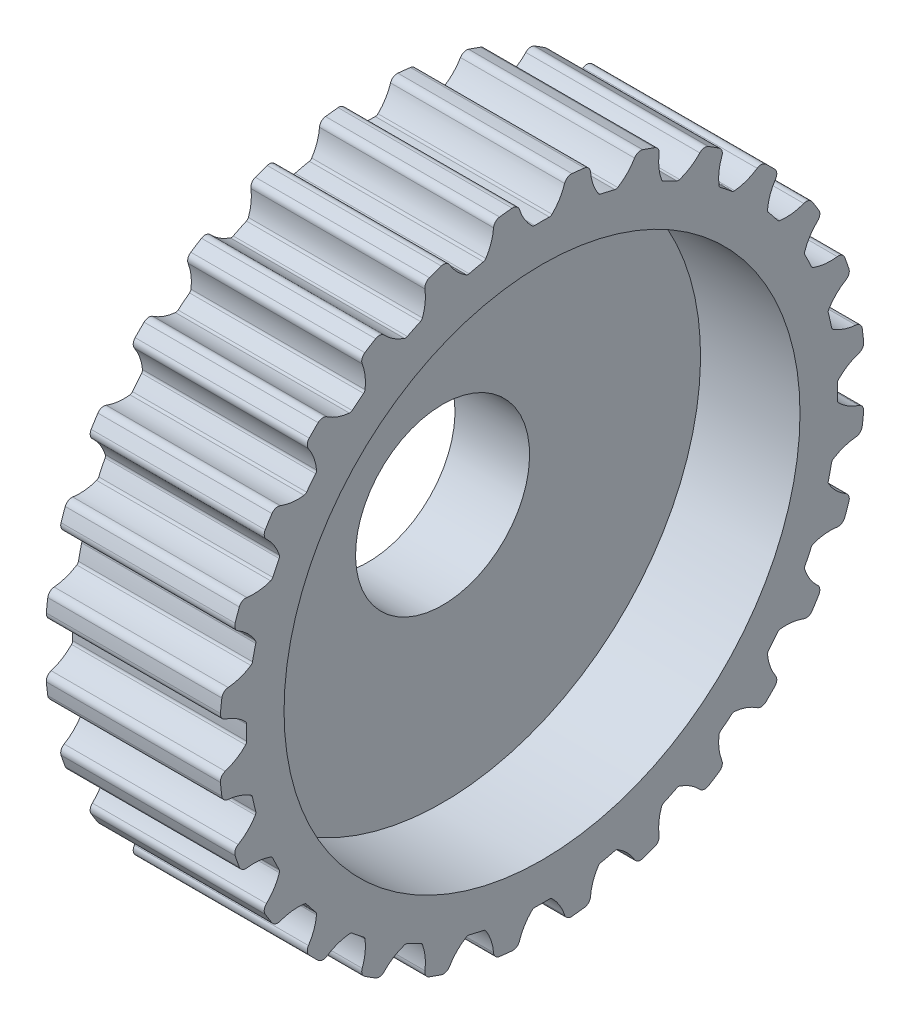
SolidWorks part; units mm, degrees
material "Vero PureWhite"
ref_plane "前视基准面" through (0, 0, 0) normal (0, 0, 1) x (1, 0, 0)
ref_plane "上视基准面" through (0, 0, 0) normal (0, 1, 0) x (1, 0, 0)
ref_plane "右视基准面" through (0, 0, 0) normal (1, 0, 0) x (0, 0, -1)
other "Configuration Table"
ref_plane "基准面1" through (0, 0, 0) normal (0, 0, 1) x (1, 0, 0)
sketch "草图1" plane through (0, 0, 0) normal (0, 0, 1) x (1, 0, 0)
  line L0 (0, 0) -> (0, 10)
  line L1 (0, 10) -> (1, 10)
  line L2 (1, 10) -> (1, 12.8583)
  line L3 (1, 12.8583) -> (0.4955, 14.7412)
  line L4 (0.4955, 14.7412) -> (1.4614, 15)
  line L5 (1.4614, 15) -> (2, 12.99)
  line L6 (2, 12.99) -> (9, 12.99)
  line L7 (9, 12.99) -> (9.5386, 15)
  line L8 (9.5386, 15) -> (10.5045, 14.7412)
  line L9 (10.5045, 14.7412) -> (10, 12.8583)
  line L10 (10, 12.8583) -> (10, 10)
  line L11 (10, 10) -> (11, 10)
  line L12 (11, 10) -> (11, 0)
  line L13 (11, 0) -> (0, 0)
  line L14 (11, 0) -> (0, 0) construction
revolve "旋转1" add sketch "草图1" angle 360 about L14
ref_plane "基准面2" through (0, 0, 0) normal (0, 0, 1) x (1, 0, 0)
sketch "草图2" plane through (0, 0, 0) normal (0, 0, 1) x (1, 0, 0)
  line L0 (0, 0) -> (0, 3.5)
  line L1 (0, 3.5) -> (11, 3.5)
  line L2 (11, 3.5) -> (11, 0)
  line L3 (11, 0) -> (0, 0)
  line L4 (11, 0) -> (0, 0) construction
  point P4 (0, 0)
  point P6 (0, 3.5)
  point P7 (10.9, 0.0386)
  point P9 (10.9, 0)
  point P10 (11, 0)
  point P11 (10.9, 3.3)
  point P13 (11, 3.3)
  point P14 (11, 3.5)
  dimension "D1" = 3.5
revolve "切除-旋转1" cut sketch "草图2" angle 360 about L4
ref_plane "基准面3" through (2, 0, 0) normal (1, 0, 0) x (0, 0, -1)
sketch "草图3" plane through (2, 0, 0) normal (1, 0, 0) x (0, 0, -1)
  circle A0 centre (0, 0) radius 17.99
  arc A1 (-12.9343, 1.2013) -> (-12.7398, 0.9084) centre (-12.6555, 1.1754) ccw
  arc A2 (-12.7398, 0.9084) -> (-11.9188, 0.4022) centre (-13.3344, -0.975) cw
  arc A3 (-11.9188, 0.4022) -> (-11.8764, 0.2939) centre (-12.0263, 0.2976) cw
  arc A4 (-11.8764, 0.2939) -> (-11.8764, -0.2939) centre (0, 0) ccw
  arc A5 (-11.8764, -0.2939) -> (-11.9188, -0.4022) centre (-12.0263, -0.2976) cw
  arc A6 (-11.9188, -0.4022) -> (-12.7398, -0.9084) centre (-13.3344, 0.975) cw
  arc A7 (-12.7398, -0.9084) -> (-12.9343, -1.2013) centre (-12.6555, -1.1754) ccw
  arc A8 (-12.9343, -1.2013) -> (-12.8774, -1.707) centre (0, 0) ccw
  arc A9 (-12.8774, -1.707) -> (-12.6225, -1.9493) centre (-12.5998, -1.6702) ccw
  arc A10 (-12.6225, -1.9493) -> (-11.7095, -2.2601) centre (-12.7831, -3.9177) cw
  arc A11 (-11.7095, -2.2601) -> (-11.644, -2.3562) centre (-11.791, -2.386) cw
  arc A12 (-11.644, -2.3562) -> (-11.5132, -2.9293) centre (0, 0) ccw
  arc A13 (-11.5132, -2.9293) -> (-11.5305, -3.0443) centre (-11.6586, -2.9663) cw
  arc A14 (-11.5305, -3.0443) -> (-12.2183, -3.7205) centre (-13.217, -2.0166) cw
  arc A15 (-12.2183, -3.7205) -> (-12.3427, -4.0493) centre (-12.0767, -3.962) ccw
  arc A16 (-12.3427, -4.0493) -> (-12.1746, -4.5297) centre (0, 0) ccw
  arc A17 (-12.1746, -4.5297) -> (-11.8723, -4.7092) centre (-11.9122, -4.432) ccw
  arc A18 (-11.8723, -4.7092) -> (-10.913, -4.809) centre (-11.5908, -6.664) cw
  arc A19 (-10.913, -4.809) -> (-10.8278, -4.8882) centre (-10.9645, -4.9499) cw
  arc A20 (-10.8278, -4.8882) -> (-10.5727, -5.4178) centre (0, 0) ccw
  arc A21 (-10.5727, -5.4178) -> (-10.564, -5.5338) centre (-10.7062, -5.4862) cw
  arc A22 (-10.564, -5.5338) -> (-11.0841, -6.346) centre (-12.4369, -4.9071) cw
  arc A23 (-11.0841, -6.346) -> (-11.1322, -6.6943) centre (-10.8923, -6.55) ccw
  arc A24 (-11.1322, -6.6943) -> (-10.8615, -7.1252) centre (0, 0) ccw
  arc A25 (-10.8615, -7.1252) -> (-10.5268, -7.233) centre (-10.6273, -6.9716) ccw
  arc A26 (-10.5268, -7.233) -> (-9.5693, -7.1168) centre (-9.8174, -9.0761) cw
  arc A27 (-9.5693, -7.1168) -> (-9.4686, -7.175) centre (-9.5881, -7.2656) cw
  arc A28 (-9.4686, -7.175) -> (-9.1021, -7.6346) centre (0, 0) ccw
  arc A29 (-9.1021, -7.6346) -> (-9.0677, -7.7457) centre (-9.217, -7.731) cw
  arc A30 (-9.0677, -7.7457) -> (-9.394, -8.6534) centre (-11.0332, -7.5516) cw
  arc A31 (-9.394, -8.6534) -> (-9.3635, -9.0036) centre (-9.1617, -8.8096) ccw
  arc A32 (-9.3635, -9.0036) -> (-9.0036, -9.3635) centre (0, 0) ccw
  arc A33 (-9.0036, -9.3635) -> (-8.6534, -9.394) centre (-8.8096, -9.1617) ccw
  arc A34 (-8.6534, -9.394) -> (-7.7457, -9.0677) centre (-7.5516, -11.0332) cw
  arc A35 (-7.7457, -9.0677) -> (-7.6346, -9.1021) centre (-7.731, -9.217) cw
  arc A36 (-7.6346, -9.1021) -> (-7.175, -9.4686) centre (0, 0) ccw
  arc A37 (-7.175, -9.4686) -> (-7.1168, -9.5693) centre (-7.2656, -9.5881) cw
  arc A38 (-7.1168, -9.5693) -> (-7.233, -10.5268) centre (-9.0761, -9.8174) cw
  arc A39 (-7.233, -10.5268) -> (-7.1252, -10.8615) centre (-6.9716, -10.6273) ccw
  arc A40 (-7.1252, -10.8615) -> (-6.6943, -11.1322) centre (0, 0) ccw
  arc A41 (-6.6943, -11.1322) -> (-6.346, -11.0841) centre (-6.55, -10.8923) ccw
  arc A42 (-6.346, -11.0841) -> (-5.5338, -10.564) centre (-4.9071, -12.4369) cw
  arc A43 (-5.5338, -10.564) -> (-5.4178, -10.5727) centre (-5.4862, -10.7062) cw
  arc A44 (-5.4178, -10.5727) -> (-4.8882, -10.8278) centre (0, 0) ccw
  arc A45 (-4.8882, -10.8278) -> (-4.809, -10.913) centre (-4.9499, -10.9645) cw
  arc A46 (-4.809, -10.913) -> (-4.7092, -11.8723) centre (-6.664, -11.5908) cw
  arc A47 (-4.7092, -11.8723) -> (-4.5297, -12.1746) centre (-4.432, -11.9122) ccw
  arc A48 (-4.5297, -12.1746) -> (-4.0493, -12.3427) centre (0, 0) ccw
  arc A49 (-4.0493, -12.3427) -> (-3.7205, -12.2183) centre (-3.962, -12.0767) ccw
  arc A50 (-3.7205, -12.2183) -> (-3.0443, -11.5305) centre (-2.0166, -13.217) cw
  arc A51 (-3.0443, -11.5305) -> (-2.9293, -11.5132) centre (-2.9663, -11.6586) cw
  arc A52 (-2.9293, -11.5132) -> (-2.3562, -11.644) centre (0, 0) ccw
  arc A53 (-2.3562, -11.644) -> (-2.2601, -11.7095) centre (-2.386, -11.791) cw
  arc A54 (-2.2601, -11.7095) -> (-1.9493, -12.6225) centre (-3.9177, -12.7831) cw
  arc A55 (-1.9493, -12.6225) -> (-1.707, -12.8774) centre (-1.6702, -12.5998) ccw
  arc A56 (-1.707, -12.8774) -> (-1.2013, -12.9343) centre (0, 0) ccw
  arc A57 (-1.2013, -12.9343) -> (-0.9084, -12.7398) centre (-1.1754, -12.6555) ccw
  arc A58 (-0.9084, -12.7398) -> (-0.4022, -11.9188) centre (0.975, -13.3344) cw
  arc A59 (-0.4022, -11.9188) -> (-0.2939, -11.8764) centre (-0.2976, -12.0263) cw
  arc A60 (-0.2939, -11.8764) -> (0.2939, -11.8764) centre (0, 0) ccw
  arc A61 (0.2939, -11.8764) -> (0.4022, -11.9188) centre (0.2976, -12.0263) cw
  arc A62 (0.4022, -11.9188) -> (0.9084, -12.7398) centre (-0.975, -13.3344) cw
  arc A63 (0.9084, -12.7398) -> (1.2013, -12.9343) centre (1.1754, -12.6555) ccw
  arc A64 (1.2013, -12.9343) -> (1.707, -12.8774) centre (0, 0) ccw
  arc A65 (1.707, -12.8774) -> (1.9493, -12.6225) centre (1.6702, -12.5998) ccw
  arc A66 (1.9493, -12.6225) -> (2.2601, -11.7095) centre (3.9177, -12.7831) cw
  arc A67 (2.2601, -11.7095) -> (2.3562, -11.644) centre (2.386, -11.791) cw
  arc A68 (2.3562, -11.644) -> (2.9293, -11.5132) centre (0, 0) ccw
  arc A69 (2.9293, -11.5132) -> (3.0443, -11.5305) centre (2.9663, -11.6586) cw
  arc A70 (3.0443, -11.5305) -> (3.7205, -12.2183) centre (2.0166, -13.217) cw
  arc A71 (3.7205, -12.2183) -> (4.0493, -12.3427) centre (3.962, -12.0767) ccw
  arc A72 (4.0493, -12.3427) -> (4.5297, -12.1746) centre (0, 0) ccw
  arc A73 (4.5297, -12.1746) -> (4.7092, -11.8723) centre (4.432, -11.9122) ccw
  arc A74 (4.7092, -11.8723) -> (4.809, -10.913) centre (6.664, -11.5908) cw
  arc A75 (4.809, -10.913) -> (4.8882, -10.8278) centre (4.9499, -10.9645) cw
  arc A76 (4.8882, -10.8278) -> (5.4178, -10.5727) centre (0, 0) ccw
  arc A77 (5.4178, -10.5727) -> (5.5338, -10.564) centre (5.4862, -10.7062) cw
  arc A78 (5.5338, -10.564) -> (6.346, -11.0841) centre (4.9071, -12.4369) cw
  arc A79 (6.346, -11.0841) -> (6.6943, -11.1322) centre (6.55, -10.8923) ccw
  arc A80 (6.6943, -11.1322) -> (7.1252, -10.8615) centre (0, 0) ccw
  arc A81 (7.1252, -10.8615) -> (7.233, -10.5268) centre (6.9716, -10.6273) ccw
  arc A82 (7.233, -10.5268) -> (7.1168, -9.5693) centre (9.0761, -9.8174) cw
  arc A83 (7.1168, -9.5693) -> (7.175, -9.4686) centre (7.2656, -9.5881) cw
  arc A84 (7.175, -9.4686) -> (7.6346, -9.1021) centre (0, 0) ccw
  arc A85 (7.6346, -9.1021) -> (7.7457, -9.0677) centre (7.731, -9.217) cw
  arc A86 (7.7457, -9.0677) -> (8.6534, -9.394) centre (7.5516, -11.0332) cw
  arc A87 (8.6534, -9.394) -> (9.0036, -9.3635) centre (8.8096, -9.1617) ccw
  arc A88 (9.0036, -9.3635) -> (9.3635, -9.0036) centre (0, 0) ccw
  arc A89 (9.3635, -9.0036) -> (9.394, -8.6534) centre (9.1617, -8.8096) ccw
  arc A90 (9.394, -8.6534) -> (9.0677, -7.7457) centre (11.0332, -7.5516) cw
  arc A91 (9.0677, -7.7457) -> (9.1021, -7.6346) centre (9.217, -7.731) cw
  arc A92 (9.1021, -7.6346) -> (9.4686, -7.175) centre (0, 0) ccw
  arc A93 (9.4686, -7.175) -> (9.5693, -7.1168) centre (9.5881, -7.2656) cw
  arc A94 (9.5693, -7.1168) -> (10.5268, -7.233) centre (9.8174, -9.0761) cw
  arc A95 (10.5268, -7.233) -> (10.8615, -7.1252) centre (10.6273, -6.9716) ccw
  arc A96 (10.8615, -7.1252) -> (11.1322, -6.6943) centre (0, 0) ccw
  arc A97 (11.1322, -6.6943) -> (11.0841, -6.346) centre (10.8923, -6.55) ccw
  arc A98 (11.0841, -6.346) -> (10.564, -5.5338) centre (12.4369, -4.9071) cw
  arc A99 (10.564, -5.5338) -> (10.5727, -5.4178) centre (10.7062, -5.4862) cw
  arc A100 (10.5727, -5.4178) -> (10.8278, -4.8882) centre (0, 0) ccw
  arc A101 (10.8278, -4.8882) -> (10.913, -4.809) centre (10.9645, -4.9499) cw
  arc A102 (10.913, -4.809) -> (11.8723, -4.7092) centre (11.5908, -6.664) cw
  arc A103 (11.8723, -4.7092) -> (12.1746, -4.5297) centre (11.9122, -4.432) ccw
  arc A104 (12.1746, -4.5297) -> (12.3427, -4.0493) centre (0, 0) ccw
  arc A105 (12.3427, -4.0493) -> (12.2183, -3.7205) centre (12.0767, -3.962) ccw
  arc A106 (12.2183, -3.7205) -> (11.5305, -3.0443) centre (13.217, -2.0166) cw
  arc A107 (11.5305, -3.0443) -> (11.5132, -2.9293) centre (11.6586, -2.9663) cw
  arc A108 (11.5132, -2.9293) -> (11.644, -2.3562) centre (0, 0) ccw
  arc A109 (11.644, -2.3562) -> (11.7095, -2.2601) centre (11.791, -2.386) cw
  arc A110 (11.7095, -2.2601) -> (12.6225, -1.9493) centre (12.7831, -3.9177) cw
  arc A111 (12.6225, -1.9493) -> (12.8774, -1.707) centre (12.5998, -1.6702) ccw
  arc A112 (12.8774, -1.707) -> (12.9343, -1.2013) centre (0, 0) ccw
  arc A113 (12.9343, -1.2013) -> (12.7398, -0.9084) centre (12.6555, -1.1754) ccw
  arc A114 (12.7398, -0.9084) -> (11.9188, -0.4022) centre (13.3344, 0.975) cw
  arc A115 (11.9188, -0.4022) -> (11.8764, -0.2939) centre (12.0263, -0.2976) cw
  arc A116 (11.8764, -0.2939) -> (11.8764, 0.2939) centre (0, 0) ccw
  arc A117 (11.8764, 0.2939) -> (11.9188, 0.4022) centre (12.0263, 0.2976) cw
  arc A118 (11.9188, 0.4022) -> (12.7398, 0.9084) centre (13.3344, -0.975) cw
  arc A119 (12.7398, 0.9084) -> (12.9343, 1.2013) centre (12.6555, 1.1754) ccw
  arc A120 (12.9343, 1.2013) -> (12.8774, 1.707) centre (0, 0) ccw
  arc A121 (12.8774, 1.707) -> (12.6225, 1.9493) centre (12.5998, 1.6702) ccw
  arc A122 (12.6225, 1.9493) -> (11.7095, 2.2601) centre (12.7831, 3.9177) cw
  arc A123 (11.7095, 2.2601) -> (11.644, 2.3562) centre (11.791, 2.386) cw
  arc A124 (11.644, 2.3562) -> (11.5132, 2.9293) centre (0, 0) ccw
  arc A125 (11.5132, 2.9293) -> (11.5305, 3.0443) centre (11.6586, 2.9663) cw
  arc A126 (11.5305, 3.0443) -> (12.2183, 3.7205) centre (13.217, 2.0166) cw
  arc A127 (12.2183, 3.7205) -> (12.3427, 4.0493) centre (12.0767, 3.962) ccw
  arc A128 (12.3427, 4.0493) -> (12.1746, 4.5297) centre (0, 0) ccw
  arc A129 (12.1746, 4.5297) -> (11.8723, 4.7092) centre (11.9122, 4.432) ccw
  arc A130 (11.8723, 4.7092) -> (10.913, 4.809) centre (11.5908, 6.664) cw
  arc A131 (10.913, 4.809) -> (10.8278, 4.8882) centre (10.9645, 4.9499) cw
  arc A132 (10.8278, 4.8882) -> (10.5727, 5.4178) centre (0, 0) ccw
  arc A133 (10.5727, 5.4178) -> (10.564, 5.5338) centre (10.7062, 5.4862) cw
  arc A134 (10.564, 5.5338) -> (11.0841, 6.346) centre (12.4369, 4.9071) cw
  arc A135 (11.0841, 6.346) -> (11.1322, 6.6943) centre (10.8923, 6.55) ccw
  arc A136 (11.1322, 6.6943) -> (10.8615, 7.1252) centre (0, 0) ccw
  arc A137 (10.8615, 7.1252) -> (10.5268, 7.233) centre (10.6273, 6.9716) ccw
  arc A138 (10.5268, 7.233) -> (9.5693, 7.1168) centre (9.8174, 9.0761) cw
  arc A139 (9.5693, 7.1168) -> (9.4686, 7.175) centre (9.5881, 7.2656) cw
  arc A140 (9.4686, 7.175) -> (9.1021, 7.6346) centre (0, 0) ccw
  arc A141 (9.1021, 7.6346) -> (9.0677, 7.7457) centre (9.217, 7.731) cw
  arc A142 (9.0677, 7.7457) -> (9.394, 8.6534) centre (11.0332, 7.5516) cw
  arc A143 (9.394, 8.6534) -> (9.3635, 9.0036) centre (9.1617, 8.8096) ccw
  arc A144 (9.3635, 9.0036) -> (9.0036, 9.3635) centre (0, 0) ccw
  arc A145 (9.0036, 9.3635) -> (8.6534, 9.394) centre (8.8096, 9.1617) ccw
  arc A146 (8.6534, 9.394) -> (7.7457, 9.0677) centre (7.5516, 11.0332) cw
  arc A147 (7.7457, 9.0677) -> (7.6346, 9.1021) centre (7.731, 9.217) cw
  arc A148 (7.6346, 9.1021) -> (7.175, 9.4686) centre (0, 0) ccw
  arc A149 (7.175, 9.4686) -> (7.1168, 9.5693) centre (7.2656, 9.5881) cw
  arc A150 (7.1168, 9.5693) -> (7.233, 10.5268) centre (9.0761, 9.8174) cw
  arc A151 (7.233, 10.5268) -> (7.1252, 10.8615) centre (6.9716, 10.6273) ccw
  arc A152 (7.1252, 10.8615) -> (6.6943, 11.1322) centre (0, 0) ccw
  arc A153 (6.6943, 11.1322) -> (6.346, 11.0841) centre (6.55, 10.8923) ccw
  arc A154 (6.346, 11.0841) -> (5.5338, 10.564) centre (4.9071, 12.4369) cw
  arc A155 (5.5338, 10.564) -> (5.4178, 10.5727) centre (5.4862, 10.7062) cw
  arc A156 (5.4178, 10.5727) -> (4.8882, 10.8278) centre (0, 0) ccw
  arc A157 (4.8882, 10.8278) -> (4.809, 10.913) centre (4.9499, 10.9645) cw
  arc A158 (4.809, 10.913) -> (4.7092, 11.8723) centre (6.664, 11.5908) cw
  arc A159 (4.7092, 11.8723) -> (4.5297, 12.1746) centre (4.432, 11.9122) ccw
  arc A160 (4.5297, 12.1746) -> (4.0493, 12.3427) centre (0, 0) ccw
  arc A161 (4.0493, 12.3427) -> (3.7205, 12.2183) centre (3.962, 12.0767) ccw
  arc A162 (3.7205, 12.2183) -> (3.0443, 11.5305) centre (2.0166, 13.217) cw
  arc A163 (3.0443, 11.5305) -> (2.9293, 11.5132) centre (2.9663, 11.6586) cw
  arc A164 (2.9293, 11.5132) -> (2.3562, 11.644) centre (0, 0) ccw
  arc A165 (2.3562, 11.644) -> (2.2601, 11.7095) centre (2.386, 11.791) cw
  arc A166 (2.2601, 11.7095) -> (1.9493, 12.6225) centre (3.9177, 12.7831) cw
  arc A167 (1.9493, 12.6225) -> (1.707, 12.8774) centre (1.6702, 12.5998) ccw
  arc A168 (1.707, 12.8774) -> (1.2013, 12.9343) centre (0, 0) ccw
  arc A169 (1.2013, 12.9343) -> (0.9084, 12.7398) centre (1.1754, 12.6555) ccw
  arc A170 (0.9084, 12.7398) -> (0.4022, 11.9188) centre (-0.975, 13.3344) cw
  arc A171 (0.4022, 11.9188) -> (0.2939, 11.8764) centre (0.2976, 12.0263) cw
  arc A172 (0.2939, 11.8764) -> (-0.2939, 11.8764) centre (0, 0) ccw
  arc A173 (-0.2939, 11.8764) -> (-0.4022, 11.9188) centre (-0.2976, 12.0263) cw
  arc A174 (-0.4022, 11.9188) -> (-0.9084, 12.7398) centre (0.975, 13.3344) cw
  arc A175 (-0.9084, 12.7398) -> (-1.2013, 12.9343) centre (-1.1754, 12.6555) ccw
  arc A176 (-1.2013, 12.9343) -> (-1.707, 12.8774) centre (0, 0) ccw
  arc A177 (-1.707, 12.8774) -> (-1.9493, 12.6225) centre (-1.6702, 12.5998) ccw
  arc A178 (-1.9493, 12.6225) -> (-2.2601, 11.7095) centre (-3.9177, 12.7831) cw
  arc A179 (-2.2601, 11.7095) -> (-2.3562, 11.644) centre (-2.386, 11.791) cw
  arc A180 (-2.3562, 11.644) -> (-2.9293, 11.5132) centre (0, 0) ccw
  arc A181 (-2.9293, 11.5132) -> (-3.0443, 11.5305) centre (-2.9663, 11.6586) cw
  arc A182 (-3.0443, 11.5305) -> (-3.7205, 12.2183) centre (-2.0166, 13.217) cw
  arc A183 (-3.7205, 12.2183) -> (-4.0493, 12.3427) centre (-3.962, 12.0767) ccw
  arc A184 (-4.0493, 12.3427) -> (-4.5297, 12.1746) centre (0, 0) ccw
  arc A185 (-4.5297, 12.1746) -> (-4.7092, 11.8723) centre (-4.432, 11.9122) ccw
  arc A186 (-4.7092, 11.8723) -> (-4.809, 10.913) centre (-6.664, 11.5908) cw
  arc A187 (-4.809, 10.913) -> (-4.8882, 10.8278) centre (-4.9499, 10.9645) cw
  arc A188 (-4.8882, 10.8278) -> (-5.4178, 10.5727) centre (0, 0) ccw
  arc A189 (-5.4178, 10.5727) -> (-5.5338, 10.564) centre (-5.4862, 10.7062) cw
  arc A190 (-5.5338, 10.564) -> (-6.346, 11.0841) centre (-4.9071, 12.4369) cw
  arc A191 (-6.346, 11.0841) -> (-6.6943, 11.1322) centre (-6.55, 10.8923) ccw
  arc A192 (-6.6943, 11.1322) -> (-7.1252, 10.8615) centre (0, 0) ccw
  arc A193 (-7.1252, 10.8615) -> (-7.233, 10.5268) centre (-6.9716, 10.6273) ccw
  arc A194 (-7.233, 10.5268) -> (-7.1168, 9.5693) centre (-9.0761, 9.8174) cw
  arc A195 (-7.1168, 9.5693) -> (-7.175, 9.4686) centre (-7.2656, 9.5881) cw
  arc A196 (-7.175, 9.4686) -> (-7.6346, 9.1021) centre (0, 0) ccw
  arc A197 (-7.6346, 9.1021) -> (-7.7457, 9.0677) centre (-7.731, 9.217) cw
  arc A198 (-7.7457, 9.0677) -> (-8.6534, 9.394) centre (-7.5516, 11.0332) cw
  arc A199 (-8.6534, 9.394) -> (-9.0036, 9.3635) centre (-8.8096, 9.1617) ccw
  arc A200 (-9.0036, 9.3635) -> (-9.3635, 9.0036) centre (0, 0) ccw
  arc A201 (-9.3635, 9.0036) -> (-9.394, 8.6534) centre (-9.1617, 8.8096) ccw
  arc A202 (-9.394, 8.6534) -> (-9.0677, 7.7457) centre (-11.0332, 7.5516) cw
  arc A203 (-9.0677, 7.7457) -> (-9.1021, 7.6346) centre (-9.217, 7.731) cw
  arc A204 (-9.1021, 7.6346) -> (-9.4686, 7.175) centre (0, 0) ccw
  arc A205 (-9.4686, 7.175) -> (-9.5693, 7.1168) centre (-9.5881, 7.2656) cw
  arc A206 (-9.5693, 7.1168) -> (-10.5268, 7.233) centre (-9.8174, 9.0761) cw
  arc A207 (-10.5268, 7.233) -> (-10.8615, 7.1252) centre (-10.6273, 6.9716) ccw
  arc A208 (-10.8615, 7.1252) -> (-11.1322, 6.6943) centre (0, 0) ccw
  arc A209 (-11.1322, 6.6943) -> (-11.0841, 6.346) centre (-10.8923, 6.55) ccw
  arc A210 (-11.0841, 6.346) -> (-10.564, 5.5338) centre (-12.4369, 4.9071) cw
  arc A211 (-10.564, 5.5338) -> (-10.5727, 5.4178) centre (-10.7062, 5.4862) cw
  arc A212 (-10.5727, 5.4178) -> (-10.8278, 4.8882) centre (0, 0) ccw
  arc A213 (-10.8278, 4.8882) -> (-10.913, 4.809) centre (-10.9645, 4.9499) cw
  arc A214 (-10.913, 4.809) -> (-11.8723, 4.7092) centre (-11.5908, 6.664) cw
  arc A215 (-11.8723, 4.7092) -> (-12.1746, 4.5297) centre (-11.9122, 4.432) ccw
  arc A216 (-12.1746, 4.5297) -> (-12.3427, 4.0493) centre (0, 0) ccw
  arc A217 (-12.3427, 4.0493) -> (-12.2183, 3.7205) centre (-12.0767, 3.962) ccw
  arc A218 (-12.2183, 3.7205) -> (-11.5305, 3.0443) centre (-13.217, 2.0166) cw
  arc A219 (-11.5305, 3.0443) -> (-11.5132, 2.9293) centre (-11.6586, 2.9663) cw
  arc A220 (-11.5132, 2.9293) -> (-11.644, 2.3562) centre (0, 0) ccw
  arc A221 (-11.644, 2.3562) -> (-11.7095, 2.2601) centre (-11.791, 2.386) cw
  arc A222 (-11.7095, 2.2601) -> (-12.6225, 1.9493) centre (-12.7831, 3.9177) cw
  arc A223 (-12.6225, 1.9493) -> (-12.8774, 1.707) centre (-12.5998, 1.6702) ccw
  arc A224 (-12.8774, 1.707) -> (-12.9343, 1.2013) centre (0, 0) ccw
extrude "切除-拉伸1" cut sketch "草图3" along normal blind 7
sketch "草图4" plane through (0, 0, 0) normal (0, 0, 1) x (1, 0, 0)
  line L1 (-9.3365, 55.092) -> (2, 55.092)
  line L2 (-9.3365, 55.092) -> (-9.3365, -19.7557)
  line L3 (-9.3365, -19.7557) -> (2, -19.7557)
  line L4 (2, 55.092) -> (2, -19.7557)
  line L5 (-9.3365, 55.092) -> (2, -19.7557) construction
  line L6 (-9.3365, -19.7557) -> (2, 55.092) construction
  line L7 (24.9109, 51.9429) -> (9, 51.9429)
  line L8 (24.9109, 51.9429) -> (24.9109, -20.1203)
  line L9 (24.9109, -20.1203) -> (9, -20.1203)
  line L10 (9, 51.9429) -> (9, -20.1203)
  line L11 (24.9109, 51.9429) -> (9, -20.1203) construction
  line L12 (24.9109, -20.1203) -> (9, 51.9429) construction
  point P0 (-3.6683, 17.6681)
  point P5 (16.9555, 15.9113)
extrude "切除-拉伸2" cut sketch "草图4" against normal through all both and the other way through all
sketch "草图5" plane through (9, 0, 0) normal (1, 0, 0) x (0, 0, -1)
  circle A0 centre (0, 0) radius 10.375
  dimension "D1" = 20.75
extrude "切除-拉伸3" cut sketch "草图5" against normal offset from surface 3 and the other way through all up to face at (2, 3.5, 0)
